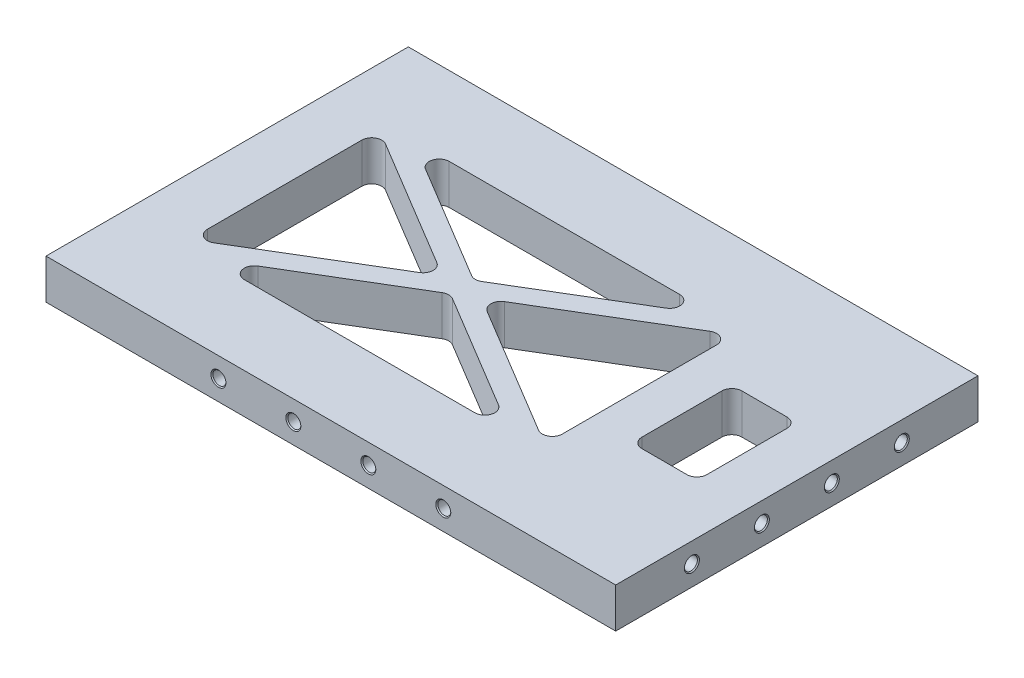
SolidWorks part; units mm, degrees
ref_plane "前基準面" through (0, 0, 0) normal (0, 0, 1) x (1, 0, 0)
ref_plane "上基準面" through (0, 0, 0) normal (0, 1, 0) x (1, 0, 0)
ref_plane "右基準面" through (0, 0, 0) normal (1, 0, 0) x (0, 0, -1)
sketch "草圖1" plane through (0, 0, 0) normal (0, 1, 0) x (1, 0, 0)
  line L1 (-57, 36.25) -> (57, 36.25)
  line L2 (-57, 36.25) -> (-57, -36.25)
  line L3 (-57, -36.25) -> (57, -36.25)
  line L4 (57, 36.25) -> (57, -36.25)
  line L5 (-57, 36.25) -> (57, -36.25) construction
  line L6 (-57, -36.25) -> (57, 36.25) construction
  point P0 (0, 0)
  dimension "D1" = 72.5
  dimension "D2" = 114
extrude "填料-伸長1" add sketch "草圖1" along normal blind 8
sketch "草圖2" plane through (0, 0, 36.25) normal (0, 0, 1) x (1, 0, 0)
  line L0 (-57, 8) -> (-57, 0) construction
  line L1 (-57, 0) -> (57, 0) construction
  circle A0 centre (-22.5, 4) radius 1.3
  dimension "D1" = 2.6
  dimension "D2" = 34.5
  dimension "D3" = 4
extrude "除料-伸長1" cut sketch "草圖2" against normal blind 8
pattern_linear "直線複製排列1" count 4 spacing 15 along (1, 0, 0) of "除料-伸長1"
mirror "鏡射1" about plane through (0, 0, 0) normal (0, 0, 1) of "除料-伸長1", "直線複製排列1"
sketch "草圖3" plane through (-57, 0, 0) normal (-1, 0, 0) x (0, 0, 1)
  line L0 (-36.25, 8) -> (36.25, 8) construction
  line L1 (-36.25, 8) -> (-36.25, 0) construction
  circle A0 centre (-21, 4) radius 1.3
  dimension "D1" = 2.6
  dimension "D2" = 4
  dimension "D3" = 15.25
extrude "除料-伸長2" cut sketch "草圖3" against normal blind 7.5
pattern_linear "直線複製排列2" count 4 spacing 14 along (0, 0, 1) of "除料-伸長2"
mirror "鏡射2" about plane through (0, 0, 0) normal (1, 0, 0) of "除料-伸長2", "直線複製排列2"
sketch "草圖4" plane through (0, 8, 0) normal (0, 1, 0) x (1, 0, 0)
  line L0 (57, -36.25) -> (57, 36.25) construction
  line L1 (34, 10) -> (47, 10)
  line L2 (34, 10) -> (34, -10)
  line L3 (34, -10) -> (47, -10)
  line L4 (47, 10) -> (47, -10)
  line L5 (34, 10) -> (47, -10) construction
  line L6 (34, -10) -> (47, 10) construction
  line L8 (-47.5, 22.5) -> (27.5, 22.5) construction
  line L9 (-47.5, 22.5) -> (-47.5, -22.5) construction
  line L10 (-47.5, -22.5) -> (27.5, -22.5) construction
  line L11 (27.5, 22.5) -> (27.5, -22.5) construction
  line L12 (-47.5, 22.5) -> (27.5, -22.5) construction
  line L13 (-47.5, -22.5) -> (27.5, 22.5) construction
  line L16 (-45.5, 18.9676) -> (-45.5, -18.9676)
  line L17 (-40.2794, -20.5) -> (20.2794, -20.5)
  line L18 (25.5, 18.9676) -> (25.5, -18.9676)
  line L21 (-40.2794, 20.5) -> (-10, 2.3324)
  line L22 (-6.1127, 0) -> (25.5, -18.9676)
  line L23 (-48.529, -20.785) -> (-47.5, -20.1676)
  line L24 (-46.471, 24.215) -> (28.529, -20.785) construction
  line L25 (-40.2794, 20.5) -> (20.2794, 20.5)
  line L26 (-45.5, 20.5) -> (25.5, 20.5) construction
  line L27 (-45.5, 20.5) -> (-45.5, -20.5) construction
  line L28 (-45.5, 18.9676) -> (-13.8873, 0)
  line L30 (-45.5, -18.9676) -> (-13.8873, 0)
  line L31 (-48.529, -20.785) -> (26.471, 24.215) construction
  line L32 (-45.5, -20.5) -> (25.5, -20.5) construction
  line L33 (-40.2794, -20.5) -> (-10, -2.3324)
  line L34 (25.5, 20.5) -> (25.5, -20.5) construction
  line L35 (-6.1127, 0) -> (25.5, 18.9676)
  line L36 (-10, -2.3324) -> (20.2794, -20.5)
  line L37 (-10, 2.3324) -> (20.2794, 20.5)
  point P0 (40.5, 0)
  point P7 (-10, 0)
  dimension "D1" = 20
  dimension "D2" = 13
  dimension "D3" = 10
  dimension "D4" = 10
  dimension "D5" = 75
  dimension "D6" = 45
  dimension "D7" = 2
  dimension "D10" = 2
  dimension "D12" = 2
  dimension "D8" = 2
  dimension "D9" = 2
  dimension "D11" = 2
extrude "除料-伸長3" cut sketch "草圖4" against normal up to next contours L16 L30 L28 | L21 L37 L25 | L35 L22 L18 | L36 L33 L17 | L4 L1 L2 L3
fillet "圓角1" radius 2 16 edges at (34, 4, 10) (34, 4, -10) (47, 4, -10) (47, 4, 10) (25.5, 4, 18.9676) (25.5, 4, -18.9676) (20.2794, 4, -20.5) (-40.2794, 4, -20.5) (-45.5, 4, -18.9676) (-45.5, 4, 18.9676) (-40.2794, 4, 20.5) (20.2794, 4, 20.5) (-10, 4, 2.3324) (-6.1127, 4, 0) (-10, 4, -2.3324) (-13.8873, 4, 0)
chamfer "導角1" distance 0.2 distance2 0.2 16 edges at (23.8, 4, 36.25) (8.8, 4, 36.25) (-6.2, 4, 36.25) (-21.2, 4, 36.25) (-57, 4, 22.3) (-57, 4, 8.3) (-57, 4, -5.7) (-57, 4, -19.7) (-21.2, 4, -36.25) (-6.2, 4, -36.25) (8.8, 4, -36.25) (23.8, 4, -36.25) (57, 4, -19.7) (57, 4, -5.7) (57, 4, 8.3) (57, 4, 22.3)
